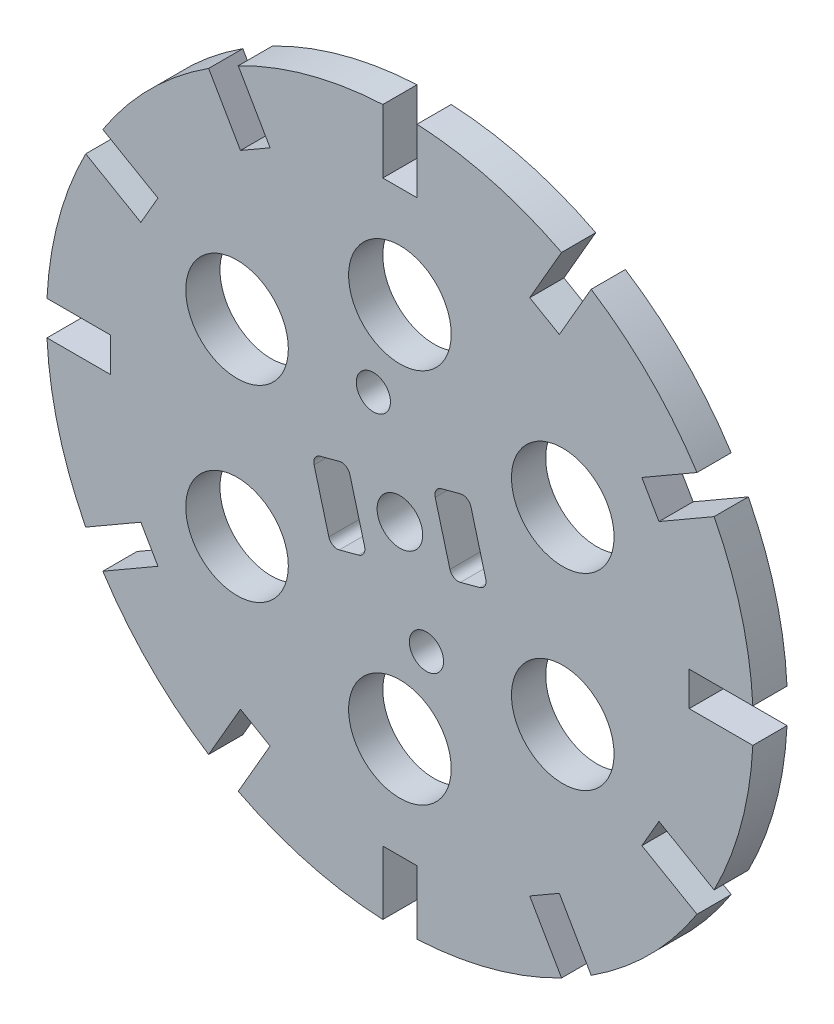
SolidWorks part; units mm, degrees
ref_plane "Alzado" through (0, 0, 0) normal (0, 0, 1) x (1, 0, 0)
ref_plane "Planta" through (0, 0, 0) normal (0, 1, 0) x (1, 0, 0)
ref_plane "Vista lateral" through (0, 0, 0) normal (1, 0, 0) x (0, 0, -1)
sketch "Model" plane through (0, 0, 0) normal (0, 0, 1) x (1, 0, 0)
  line L0 (47.3545, 269.9346) -> (45.6642, 269.4817)
  line L1 (49.5672, 264.5746) -> (48.2731, 269.4043)
  line L2 (47.3465, 263.2031) -> (49.0369, 263.6561)
  line L3 (45.1338, 268.5631) -> (46.4279, 263.7335)
  line L4 (35.039, 266.6346) -> (36.7294, 267.0876)
  line L5 (35.8027, 260.8865) -> (34.5087, 265.7161)
  line L6 (38.4117, 260.8091) -> (36.7213, 260.3561)
  line L7 (37.6479, 266.5573) -> (38.942, 261.7276)
  line L8 (53.4276, 287.8729) -> (56.2207, 292.7107)
  line L9 (53.4276, 287.8729) -> (56.0257, 286.3729)
  line L10 (56.0257, 286.3729) -> (58.8188, 291.2107)
  line L11 (63.2654, 279.1331) -> (68.1033, 281.9262)
  line L12 (63.2654, 279.1331) -> (64.7654, 276.535)
  line L13 (64.7654, 276.535) -> (69.6033, 279.3282)
  line L14 (67.4154, 266.6454) -> (73.0016, 266.6454)
  line L15 (67.4154, 266.6454) -> (67.4154, 263.6454)
  line L16 (67.4154, 263.6454) -> (73.0016, 263.6454)
  line L17 (64.7654, 253.7557) -> (69.6033, 250.9626)
  line L18 (64.7654, 253.7557) -> (63.2654, 251.1576)
  line L19 (63.2654, 251.1576) -> (68.1033, 248.3645)
  line L20 (56.0257, 243.9179) -> (58.8188, 239.08)
  line L21 (56.0257, 243.9179) -> (53.4276, 242.4179)
  line L22 (53.4276, 242.4179) -> (56.2207, 237.58)
  line L23 (43.5379, 239.7679) -> (43.5379, 234.1817)
  line L24 (43.5379, 239.7679) -> (40.5379, 239.7679)
  line L25 (40.5379, 239.7679) -> (40.5379, 234.1817)
  line L26 (30.6482, 242.4179) -> (27.8551, 237.58)
  line L27 (30.6482, 242.4179) -> (28.0502, 243.9179)
  line L28 (28.0502, 243.9179) -> (25.257, 239.08)
  line L29 (20.8104, 251.1576) -> (15.9726, 248.3645)
  line L30 (20.8104, 251.1576) -> (19.3104, 253.7557)
  line L31 (19.3104, 253.7557) -> (14.4726, 250.9626)
  line L32 (16.6605, 263.6454) -> (11.0742, 263.6454)
  line L33 (16.6605, 263.6454) -> (16.6605, 266.6454)
  line L34 (16.6605, 266.6454) -> (11.0742, 266.6454)
  line L35 (19.3104, 276.535) -> (14.4726, 279.3282)
  line L36 (19.3104, 276.535) -> (20.8104, 279.1331)
  line L37 (20.8104, 279.1331) -> (15.9726, 281.9262)
  line L38 (28.0502, 286.3729) -> (25.257, 291.2107)
  line L39 (28.0502, 286.3729) -> (30.6482, 287.8729)
  line L40 (30.6482, 287.8729) -> (27.8551, 292.7107)
  line L41 (40.5379, 290.5228) -> (40.5379, 296.109)
  line L42 (40.5379, 290.5228) -> (43.5379, 290.5228)
  line L43 (43.5379, 290.5228) -> (43.5379, 296.109)
  arc A0 (69.6033, 250.9626) -> (73.0016, 263.6454) centre (42.0379, 265.1454) ccw
  arc A1 (58.8188, 239.08) -> (68.1033, 248.3645) centre (42.0379, 265.1454) ccw
  arc A2 (43.5379, 234.1817) -> (56.2207, 237.58) centre (42.0379, 265.1454) ccw
  arc A3 (27.8551, 237.58) -> (40.5379, 234.1817) centre (42.0379, 265.1454) ccw
  arc A4 (15.9726, 248.3645) -> (25.257, 239.08) centre (42.0379, 265.1454) ccw
  arc A5 (11.0742, 263.6454) -> (14.4726, 250.9626) centre (42.0379, 265.1454) ccw
  arc A6 (25.257, 291.2107) -> (15.9726, 281.9262) centre (42.0379, 265.1454) ccw
  arc A7 (56.2207, 292.7107) -> (43.5379, 296.109) centre (42.0379, 265.1454) ccw
  arc A8 (40.5379, 296.109) -> (27.8551, 292.7107) centre (42.0379, 265.1454) ccw
  arc A9 (68.1033, 281.9262) -> (58.8188, 291.2107) centre (42.0379, 265.1454) ccw
  arc A10 (73.0016, 266.6454) -> (69.6033, 279.3282) centre (42.0379, 265.1454) ccw
  circle A11 centre (42.0379, 265.1454) radius 2
  arc A12 (45.6642, 269.4817) -> (45.1338, 268.5631) centre (45.8583, 268.7572) ccw
  arc A13 (48.2731, 269.4043) -> (47.3545, 269.9346) centre (47.5487, 269.2101) ccw
  arc A14 (49.0369, 263.6561) -> (49.5672, 264.5746) centre (48.8427, 264.3805) ccw
  arc A15 (46.4279, 263.7335) -> (47.3465, 263.2031) centre (47.1524, 263.9276) ccw
  arc A16 (37.6479, 266.5573) -> (36.7294, 267.0876) centre (36.9235, 266.3631) ccw
  arc A17 (35.039, 266.6346) -> (34.5087, 265.7161) centre (35.2331, 265.9102) ccw
  arc A18 (35.8027, 260.8865) -> (36.7213, 260.3561) centre (36.5272, 261.0806) ccw
  arc A19 (38.4117, 260.8091) -> (38.942, 261.7276) centre (38.2176, 261.5335) ccw
  circle A20 centre (39.7086, 273.8387) radius 1.5
  circle A21 centre (44.3673, 256.452) radius 1.5
  arc A22 (14.4726, 279.3282) -> (11.0742, 266.6454) centre (42.0379, 265.1454) ccw
  circle A23 centre (42.0379, 281.6441) radius 4.5
  circle A24 centre (27.7496, 273.3947) radius 4.5
  circle A25 centre (27.7496, 256.896) radius 4.5
  circle A26 centre (42.0379, 248.6466) radius 4.5
  circle A27 centre (56.3262, 256.896) radius 4.5
  circle A28 centre (56.3262, 273.3947) radius 4.5
extrude "Saliente-Extruir1" add sketch "Model" along normal blind 3
